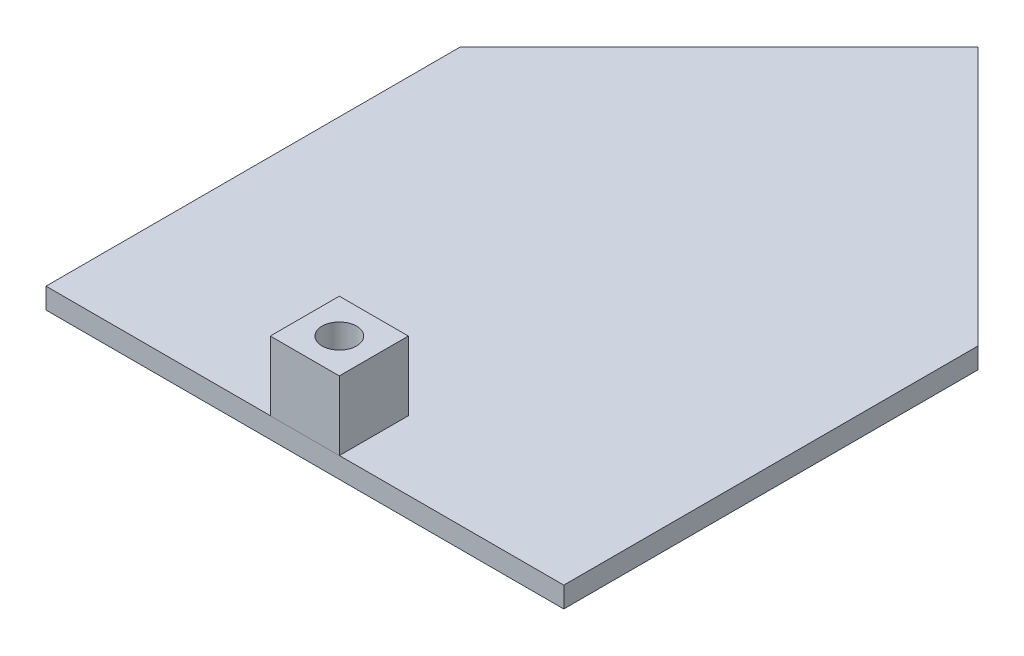
SolidWorks part; units mm, degrees
ref_plane "Front Plane" through (0, 0, 0) normal (0, 0, 1) x (1, 0, 0)
ref_plane "Top Plane" through (0, 0, 0) normal (0, 1, 0) x (1, 0, 0)
ref_plane "Right Plane" through (0, 0, 0) normal (1, 0, 0) x (0, 0, -1)
sketch "Sketch1" plane through (0, 0, 0) normal (0, 1, 0) x (1, 0, 0)
  line L0 (-34.0393, -34.1744) -> (115.9607, -34.1744)
  line L1 (115.9607, -34.1744) -> (115.9607, 85.8256)
  line L2 (115.9607, 85.8256) -> (40.9607, 160.8256)
  line L3 (40.9607, 160.8256) -> (-34.0393, 85.8256)
  line L4 (-34.0393, 85.8256) -> (-34.0393, -34.1744)
  dimension "D1" = 135
  dimension "D2" = 106.066
  dimension "D3" = 120
  dimension "D4" = 150
extrude "Boss-Extrude1" add sketch "Sketch1" along normal blind 6
sketch "Sketch2" plane through (0, 6, 0) normal (0, 1, 0) x (1, 0, 0)
  line L0 (40.9607, 160.8256) -> (40.9607, -34.1744) construction
  line L1 (-34.0393, -34.1744) -> (115.9607, -34.1744) construction
  line L2 (30.9607, -14.2064) -> (50.9607, -14.2064)
  line L3 (50.9607, -14.2064) -> (50.9607, -34.2064)
  line L4 (50.9607, -34.2064) -> (30.9607, -34.2064)
  line L5 (30.9607, -14.2064) -> (30.9607, -34.2064)
  line L6 (30.9607, -24.2064) -> (50.9607, -24.2064) construction
  circle A0 centre (40.9607, -24.2064) radius 5
  point P10 (40.9607, -34.2064)
  point P11 (40.9607, -14.2064)
  point P15 (40.9607, -23.9481)
  point P16 (40.9607, -24.2064)
  dimension "D1" = 10
  dimension "D2" = 20
  dimension "D3" = 20
extrude "Boss-Extrude2" add sketch "Sketch2" along normal blind 20
